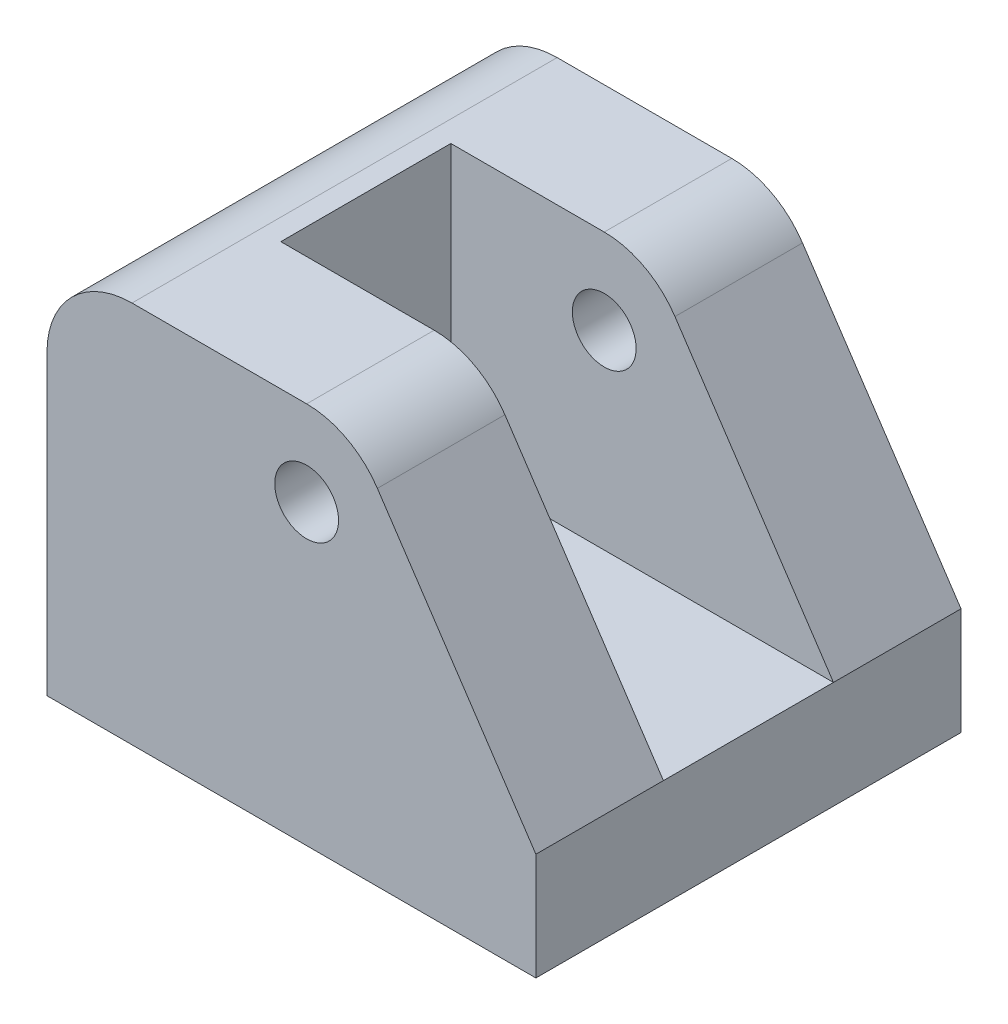
SolidWorks part; units mm, degrees
material "1023 Carbon Steel Sheet (SS)"
ref_plane "Front Plane" through (0, 0, 0) normal (0, 0, 1) x (1, 0, 0)
ref_plane "Top Plane" through (0, 0, 0) normal (0, 1, 0) x (1, 0, 0)
ref_plane "Right Plane" through (0, 0, 0) normal (1, 0, 0) x (0, 0, -1)
sketch "Sketch2" plane through (0, 0, 0) normal (0, 1, 0) x (1, 0, 0)
  line L1 (-43.1343, -163.209) -> (186.8657, -163.209)
  line L2 (-43.1343, -163.209) -> (-43.1343, 36.791)
  line L3 (-43.1343, 36.791) -> (186.8657, 36.791)
  line L4 (186.8657, -163.209) -> (186.8657, 36.791)
  dimension "D1" = 230
  dimension "D2" = 200
extrude "Boss-Extrude1" add sketch "Sketch2" along normal blind 180
sketch "Sketch3" plane through (0, 0, 163.209) normal (0, 0, 1) x (1, 0, 0)
  line L0 (-43.1343, 180) -> (186.8657, 180) construction
  line L1 (100.4226, 180) -> (186.8657, 180)
  line L2 (186.8657, 180) -> (186.8657, 0) construction
  line L3 (186.8657, 180) -> (186.8657, 50.4247)
  line L4 (100.4226, 180) -> (186.8657, 50.4247)
extrude "Cut-Extrude1" cut sketch "Sketch3" against normal blind 200
fillet "Fillet2" radius 40 2 edges at (100.4226, 180, 63.209) (-43.1343, 180, 63.209)
sketch "Sketch4" plane through (0, 0, 0) normal (0, -1, 0) x (1, 0, 0)
  circle A0 centre (71.8657, 63.209) radius 30
extrude "Cut-Extrude2" cut sketch "Sketch4" against normal blind 48
sketch "Sketch5" plane through (186.8657, 0, 0) normal (1, 0, 0) x (0, 0, -1)
  line L2 (-163.209, 180) -> (36.791, 180) construction
  line L3 (-103.209, 180) -> (-23.209, 180)
  line L4 (-103.209, 180) -> (-103.209, 50.4247)
  line L5 (-23.209, 180) -> (-23.209, 50.4247)
  line L6 (-103.209, 50.4247) -> (-23.209, 50.4247)
extrude "Cut-Extrude3" cut sketch "Sketch5" against normal blind 180
sketch "Sketch6" plane through (0, 0, 163.209) normal (0, 0, 1) x (1, 0, 0)
  arc A0 (112.2984, 162.1986) -> (79.0234, 180) centre (79.0234, 140) ccw construction
  arc A1 (112.2984, 162.1986) -> (79.0234, 180) centre (79.0234, 140) ccw
  circle A2 centre (79.0234, 140) radius 15
extrude "Cut-Extrude5" cut sketch "Sketch6" against normal blind 200 contours A2
